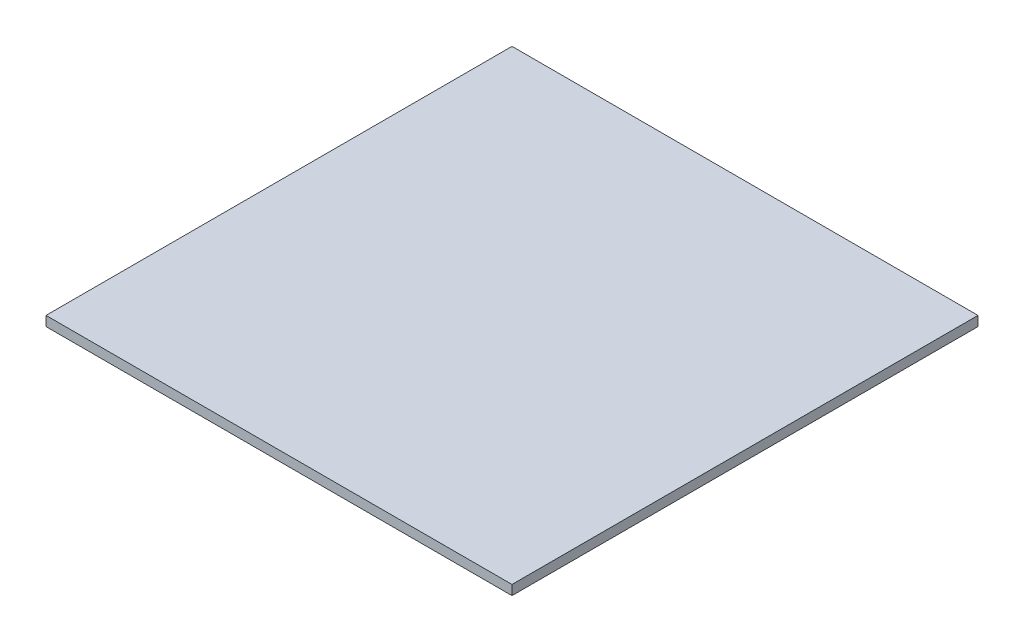
SolidWorks part; units mm, degrees
ref_plane "Front Plane" through (0, 0, 0) normal (0, 0, 1) x (1, 0, 0)
ref_plane "Top Plane" through (0, 0, 0) normal (0, 1, 0) x (1, 0, 0)
ref_plane "Right Plane" through (0, 0, 0) normal (1, 0, 0) x (0, 0, -1)
sketch "Sketch1" plane through (0, 0, 0) normal (0, 1, 0) x (1, 0, 0)
  line L1 (-609.6, -609.6) -> (609.6, -609.6)
  line L2 (-609.6, -609.6) -> (-609.6, 609.6)
  line L3 (-609.6, 609.6) -> (609.6, 609.6)
  line L4 (609.6, -609.6) -> (609.6, 609.6)
  line L5 (-609.6, -609.6) -> (609.6, 609.6) construction
  line L6 (-609.6, 609.6) -> (609.6, -609.6) construction
  point P0 (0, 0)
  dimension "D1" = 1219.2
extrude "Boss-Extrude1" add sketch "Sketch1" against normal blind 25.4
